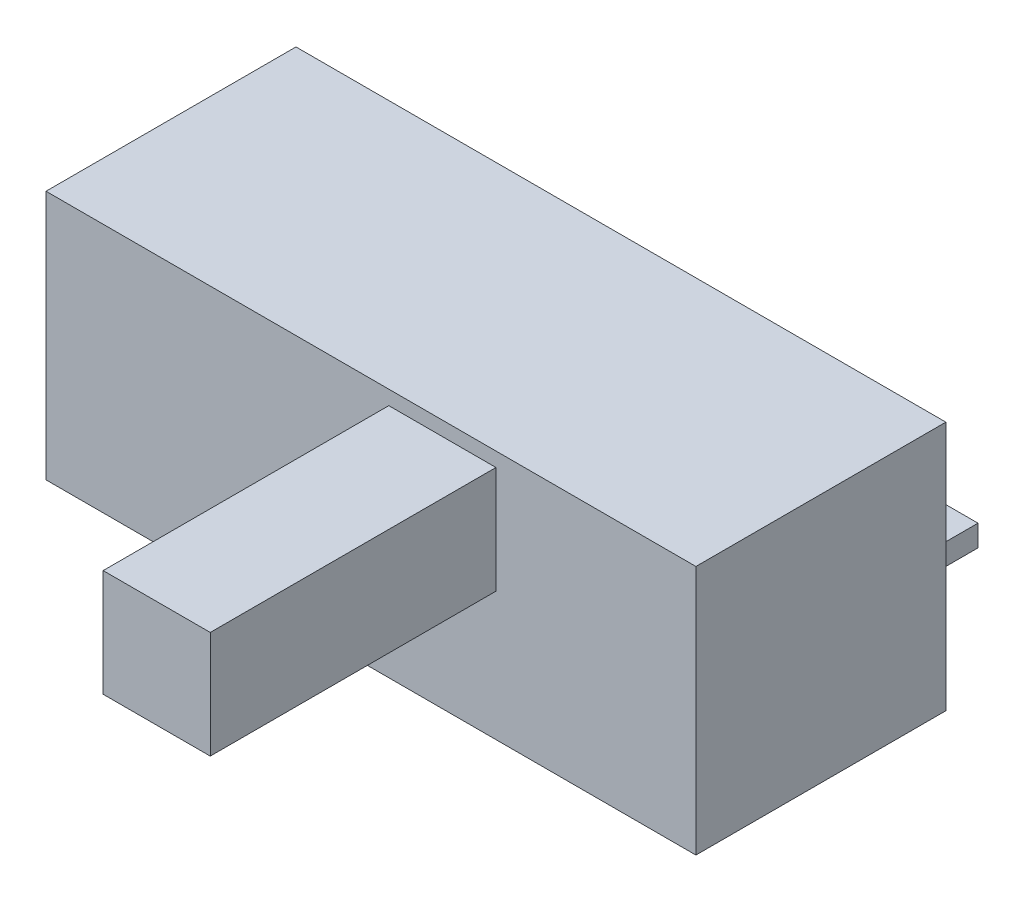
SolidWorks part; units mm, degrees
ref_plane "前视基准面" through (0, 0, 0) normal (0, 0, 1) x (1, 0, 0)
ref_plane "上视基准面" through (0, 0, 0) normal (0, 1, 0) x (1, 0, 0)
ref_plane "右视基准面" through (0, 0, 0) normal (1, 0, 0) x (0, 0, -1)
sketch "草图1" plane through (0, 0, 0) normal (0, 0, 1) x (1, 0, 0)
  line L1 (0, 0) -> (9.1, 0)
  line L2 (0, 0) -> (0, 3.5)
  line L3 (0, 3.5) -> (9.1, 3.5)
  line L4 (9.1, 0) -> (9.1, 3.5)
  dimension "D1" = 9.1
  dimension "D2" = 3.5
extrude "凸台-拉伸1" add sketch "草图1" along normal blind 3.5
sketch "草图2" plane through (0, 0, 3.5) normal (0, 0, 1) x (1, 0, 0)
  line L0 (9.1, 3.5) -> (0, 3.5) construction
  line L1 (4.8, 3.3) -> (6.3, 3.3)
  line L2 (4.8, 3.3) -> (4.8, 1.8)
  line L3 (4.8, 1.8) -> (6.3, 1.8)
  line L4 (6.3, 3.3) -> (6.3, 1.8)
  line L5 (9.1, 0) -> (9.1, 3.5) construction
  dimension "D1" = 1.5
  dimension "D2" = 0.2
  dimension "D3" = 1.5
  dimension "D4" = 2.8
extrude "凸台-拉伸2" add sketch "草图2" along normal blind 4
sketch "草图3" plane through (0, 0, 0) normal (0, -1, 0) x (1, 0, 0)
  line L0 (-0.7052, 1.75) -> (9.7536, 1.75) construction
  line L1 (4.55, 4.2202) -> (4.55, -0.4304) construction
  line L3 (0, 3.5) -> (0, 0) construction
  line L4 (9.1, 3.5) -> (9.1, 0) construction
  line L5 (0, 3.5) -> (9.1, 3.5) construction
  line L6 (0, 0) -> (9.1, 0) construction
  circle A0 centre (1.15, 1.75) radius 0.35
  circle A1 centre (7.95, 1.75) radius 0.35
  dimension "D2" = 0.7
  dimension "D1" = 6.8
extrude "凸台-拉伸3" add sketch "草图3" along normal blind 0.5
ref_plane "基准面1" through (4.55, 0, 0) normal (-1, 0, 0) x (0, 0, 1)
sketch "草图4" plane through (4.55, 0, 0) normal (-1, 0, 0) x (0, 0, 1)
  line L0 (-2.2, 3.5518) -> (-2.2, -0.5205) construction
  line L1 (0, 3.5) -> (0, 0) construction
  line L2 (-2.2, 0.15) -> (-1.0608, 0.15)
  line L3 (-1.0608, 0.15) -> (-0.7082, 0.6083)
  line L4 (-0.7082, 0.6083) -> (0, 0.6083)
  line L5 (3.5, 3.5) -> (0, 3.5) construction
  dimension "D1" = 2.2
  dimension "D2" = 3.35
ref_plane "基准面2" through (0, 0, -2.2) normal (0, 0, -1) x (-1, 0, 0)
sketch "草图5" plane through (0, 0, -2.2) normal (0, 0, -1) x (-1, 0, 0)
  line L0 (-5.1958, 0.15) -> (-3.8097, 0.15) construction
  line L1 (-4.55, 0.8027) -> (-4.55, -0.211) construction
  line L3 (-4.85, 0.3) -> (-4.25, 0.3)
  line L4 (-4.85, 0.3) -> (-4.85, 0)
  line L5 (-4.85, 0) -> (-4.25, 0)
  line L6 (-4.25, 0.3) -> (-4.25, 0)
  point P0 (-4.55, 0.15)
  dimension "D1" = 0.3
  dimension "D2" = 0.6
sweep "扫描1" add profiles "草图5" path "草图4"
pattern_linear "阵列(线性)1" count 2 spacing 2.5 along (1, 0, 0) count 2 spacing 2.5 along (-1, 0, 0) of "扫描1"
